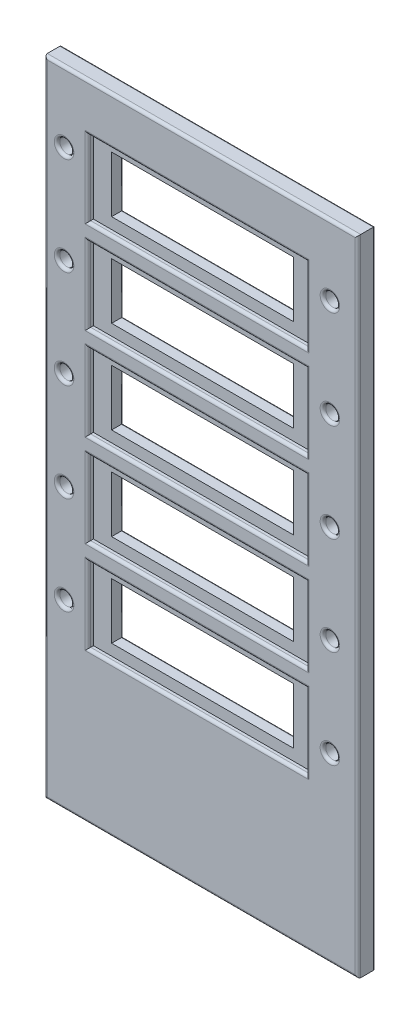
SolidWorks part; units mm, degrees
ref_plane "Alzado" through (0, 0, 0) normal (0, 0, 1) x (1, 0, 0)
ref_plane "Planta" through (0, 0, 0) normal (0, 1, 0) x (1, 0, 0)
ref_plane "Vista lateral" through (0, 0, 0) normal (1, 0, 0) x (0, 0, -1)
sketch "Croquis1" plane through (0, 0, 0) normal (0, 0, 1) x (1, 0, 0)
  line L1 (-57.5, 115) -> (57.5, 115)
  line L2 (-57.5, 115) -> (-57.5, -115)
  line L3 (-57.5, -115) -> (57.5, -115)
  line L4 (57.5, 115) -> (57.5, -115)
  line L5 (-57.5, 115) -> (57.5, -115) construction
  line L6 (-57.5, -115) -> (57.5, 115) construction
  point P0 (0, 0)
  dimension "D1" = 115
  dimension "D2" = 230
extrude "Saliente-Extruir1" add sketch "Croquis1" along normal blind 2
sketch "Croquis2" plane through (0, 0, 2) normal (0, 0, 1) x (1, 0, 0)
  line L0 (57.5, 115) -> (-57.5, 115) construction
  line L1 (-39.5, 95) -> (39.5, 95)
  line L2 (-39.5, 95) -> (-39.5, -90)
  line L3 (-39.5, -90) -> (39.5, -90)
  line L4 (39.5, 95) -> (39.5, -90)
  line L5 (-57.5, -115) -> (57.5, -115) construction
  line L7 (-57.5, 115) -> (-57.5, -115) construction
  point P0 (0, 0)
  dimension "D1" = 20
  dimension "D2" = 18
  dimension "D3" = 25
extrude "Cortar-Extruir1" cut sketch "Croquis2" against normal blind 10 contours L2 L1 L4 L3
sketch "Croquis3" plane through (0, 0, 2) normal (0, 0, 1) x (1, 0, 0)
  line L1 (-57.5, 115) -> (57.5, 115)
  line L2 (-57.5, 115) -> (-57.5, -115)
  line L3 (-57.5, -115) -> (57.5, -115)
  line L4 (57.5, 115) -> (57.5, -115)
  point P0 (0, 0)
extrude "Saliente-Extruir2" add sketch "Croquis3" along normal blind 2 and the other way blind 2
sketch "Croquis4" plane through (0, 0, 4) normal (0, 0, 1) x (1, 0, 0)
  line L0 (0, 0) -> (0, 170) construction
  line L2 (-32.5, 95) -> (32.5, 95)
  line L3 (-32.5, 95) -> (-32.5, 75)
  line L4 (-32.5, 75) -> (32.5, 75)
  line L5 (32.5, 95) -> (32.5, 75)
  line L6 (-32.5, 95) -> (32.5, 75) construction
  line L7 (-32.5, 75) -> (32.5, 95) construction
  point P3 (0, 85)
  dimension "D1" = 65
  dimension "D2" = 20
  dimension "D3" = 20
extrude "Cortar-Extruir2" cut sketch "Croquis4" against normal blind 10
pattern_linear "MatrizL1" count 5 spacing 33 along (0, -1, 0) of "Cortar-Extruir2"
sketch "Croquis5" plane through (0, 0, 4) normal (0, 0, 1) x (1, 0, 0)
  line L0 (0, 0) -> (0, 15.5781) construction
  line L1 (-54.5, 115) -> (57.5, 115)
  line L2 (-54.5, 115) -> (-54.5, -115)
  line L3 (-54.5, -115) -> (57.5, -115)
  line L4 (57.5, 115) -> (57.5, -115)
  line L5 (38.99, 98) -> (38.99, 71)
  line L6 (0, 0) -> (0, -28.2795) construction
  line L7 (-39, 98) -> (39, 98)
  line L8 (-39, 98) -> (-39, 71)
  line L9 (-39, 71) -> (39, 71)
  line L10 (39, 98) -> (39, 71)
  line L11 (-39, 98) -> (39, 71) construction
  line L12 (-39, 71) -> (39, 98) construction
  line L13 (-39.01, 98) -> (38.99, 98)
  line L14 (-39.01, 98) -> (-39.01, 71)
  line L15 (-39.01, 71) -> (38.99, 71)
  line L16 (38.99, 65) -> (38.99, 38)
  line L17 (-39.01, 65) -> (38.99, 65)
  line L18 (-39.01, 65) -> (-39.01, 38)
  line L19 (-39.01, 38) -> (38.99, 38)
  line L20 (38.99, 32) -> (38.99, 5)
  line L21 (-39.01, 32) -> (38.99, 32)
  line L22 (-39.01, 32) -> (-39.01, 5)
  line L23 (-39.01, 5) -> (38.99, 5)
  line L24 (38.99, -1) -> (38.99, -28)
  line L25 (-39.01, -1) -> (38.99, -1)
  line L26 (-39.01, -1) -> (-39.01, -28)
  line L27 (-39.01, -28) -> (38.99, -28)
  line L28 (38.99, -34) -> (38.99, -61)
  line L29 (-39.01, -34) -> (38.99, -34)
  line L30 (-39.01, -34) -> (-39.01, -61)
  line L31 (-39.01, -61) -> (38.99, -61)
  line L32 (39, 65) -> (39, 38)
  line L33 (-39, 65) -> (39, 65)
  line L34 (-39, 65) -> (-39, 38)
  line L35 (-39, 38) -> (39, 38)
  line L36 (39, 32) -> (39, 5)
  line L37 (-39, 32) -> (39, 32)
  line L38 (-39, 32) -> (-39, 5)
  line L39 (-39, 5) -> (39, 5)
  line L40 (39, -1) -> (39, -28)
  line L41 (-39, -1) -> (39, -1)
  line L42 (-39, -1) -> (-39, -28)
  line L43 (-39, -28) -> (39, -28)
  line L44 (39, -34) -> (39, -61)
  line L45 (-39, -34) -> (39, -34)
  line L46 (-39, -34) -> (-39, -61)
  line L47 (-39, -61) -> (39, -61)
  line L48 (32.5, 95) -> (-32.5, 95) construction
  line L49 (32.5, 62) -> (-32.5, 62) construction
  point P0 (0, 0)
  point P7 (0, 84.5)
  line M49 (-32.5, 62) -> (32.5, 62)
  line M54 (57.5, -115) -> (57.5, 115)
  line M55 (57.5, 115) -> (-57.5, 115)
  line M56 (-57.5, 115) -> (-57.5, -115)
  line M57 (-57.5, -115) -> (57.5, -115)
  line M61 (-32.5, 29) -> (32.5, 29)
  line M65 (-32.5, -4) -> (32.5, -4)
  line M69 (-32.5, -37) -> (32.5, -37)
  dimension "D1" = 3
  dimension "D2" = 230
  dimension "D3" = 112
  dimension "D4" = 78
  dimension "D5" = 27
  dimension "D8" = 3
  dimension "D6" = 2
  dimension "D7" = 5
extrude "Saliente-Extruir3" add sketch "Croquis5" along normal blind 2 contours L47 L31 L30 L29 L45 L44 L43 L27 L26 L25 L41 L40 L39 L23 L22 L21 L37 L36 L35 L19 L18 L17 L33 L32 L15 L14 M57 M54 M55 M56 M69 M65 M61 M49
sketch "Croquis6" plane through (0, 0, 6) normal (0, 0, 1) x (1, 0, 0)
  line L0 (0, 95) -> (0, 75) construction
  line L1 (32.5, 95) -> (-32.5, 95) construction
  line L2 (-32.5, 75) -> (32.5, 75) construction
  line L3 (0, 85) -> (-22.4504, 85)
  line L4 (57.5, -115) -> (57.5, 115) construction
  circle A0 centre (47.5, 90) radius 2.5
  circle A1 centre (-47.5, 90) radius 2.5
  dimension "D2" = 5
  dimension "D1" = 10
extrude "Cortar-Extruir3" cut sketch "Croquis6" against normal blind 5 contours A1 | A0
pattern_linear "MatrizL2" count 5 spacing 35 along (0, -1, 0) of "Cortar-Extruir3"
fillet "Redondeo1" radius 1 34 edges at (-0.005, 71, 6) (-39.01, 84.5, 6) (-0.005, 38, 6) (-39.01, 51.5, 6) (-0.005, 5, 6) (-39.01, 18.5, 6) (-0.005, -28, 6) (-39.01, -14.5, 6) (-0.005, -61, 6) (-39.01, -47.5, 6) (-0.005, -34, 6) (39, -47.5, 6) (-0.005, -1, 6) (39, -14.5, 6) (-0.005, 32, 6) (39, 18.5, 6) (-0.005, 65, 6) (39, 51.5, 6) (-0.005, 98, 6) (39, 84.5, 6) (1.5, 115, 6) (-54.5, 0, 6) (1.5, -115, 6) (57.5, 0, 6) (-45, 90, 6) (50, 90, 6) (-45, 55, 6) (-45, 20, 6) (-45, -15, 6) (-45, -50, 6) (50, 55, 6) (50, 20, 6) (50, -15, 6) (50, -50, 6)
sketch "Croquis7" plane through (0, 0, 0) normal (0, 0, -1) x (-1, 0, 0)
  circle A0 centre (-44.5, 105) radius 2.6
  circle A1 centre (-21.5, 105) radius 2.6
  circle A2 centre (24.5, 105) radius 2.6
  circle A3 centre (47.5, 105) radius 2.6
  circle A4 centre (47.5, 82) radius 2.6
  circle A5 centre (-44.5, 82) radius 2.3865
  circle A6 centre (47.5, 13) radius 2.6
  circle A7 centre (-44.5, 13) radius 2.599
  circle A8 centre (-44.5, -10) radius 2.6
  circle A9 centre (47.5, -10) radius 2.6
  circle A10 centre (47.5, -79) radius 2.6
  circle A11 centre (47.5, -102) radius 2.6
  circle A12 centre (24.5, -102) radius 2.6
  circle A13 centre (-21.5, -102) radius 2.6
  circle A14 centre (-44.5, -102) radius 2.6
  circle A15 centre (-44.5, -79) radius 2.6
extrude "Cortar-Extruir4" cut sketch "Croquis7" against normal blind 4.5
fillet "Redondeo2" radius 0.5 40 edges at (0, 115, 0) (-57.5, 0, 0) (0, -115, 0) (57.5, 0, 0) (-32.5, 85, 0) (0, 95, 0) (32.5, 85, 0) (41.9, 105, 0) (41.9, -79, 0) (41.9, -102, 0) (18.9, -102, 0) (-27.1, -102, 0) (-50.1, -102, 0) (-50.1, -79, 0) (-50.1, -10, 0) (18.9, 105, 0) (-27.1, 105, 0) (-50.1, 105, 0) (-50.1, 82, 0) (41.9, -10, 0) (41.901, 13, 0) (-50.1, 13, 0) (42.1135, 82, 0) (0, -57, 0) (-32.5, -47, 0) (0, -37, 0) (32.5, -47, 0) (0, -24, 0) (-32.5, -14, 0) (0, -4, 0) (32.5, -14, 0) (0, 9, 0) (-32.5, 19, 0) (0, 29, 0) (32.5, 19, 0) (0, 75, 0) (-32.5, 52, 0) (0, 62, 0) (32.5, 52, 0) (0, 42, 0)
sketch "Croquis8" plane through (0, 0, 6) normal (0, 0, 1) x (1, 0, 0)
  line L1 (-54.5, 115) -> (57.5, 115)
  line L2 (-54.5, 115) -> (-54.5, -115)
  line L3 (-54.5, -115) -> (57.5, -115)
  line L4 (57.5, 115) -> (57.5, -115)
extrude "Cortar-Extruir6" cut sketch "Croquis8" against normal blind 10 flip side to cut
